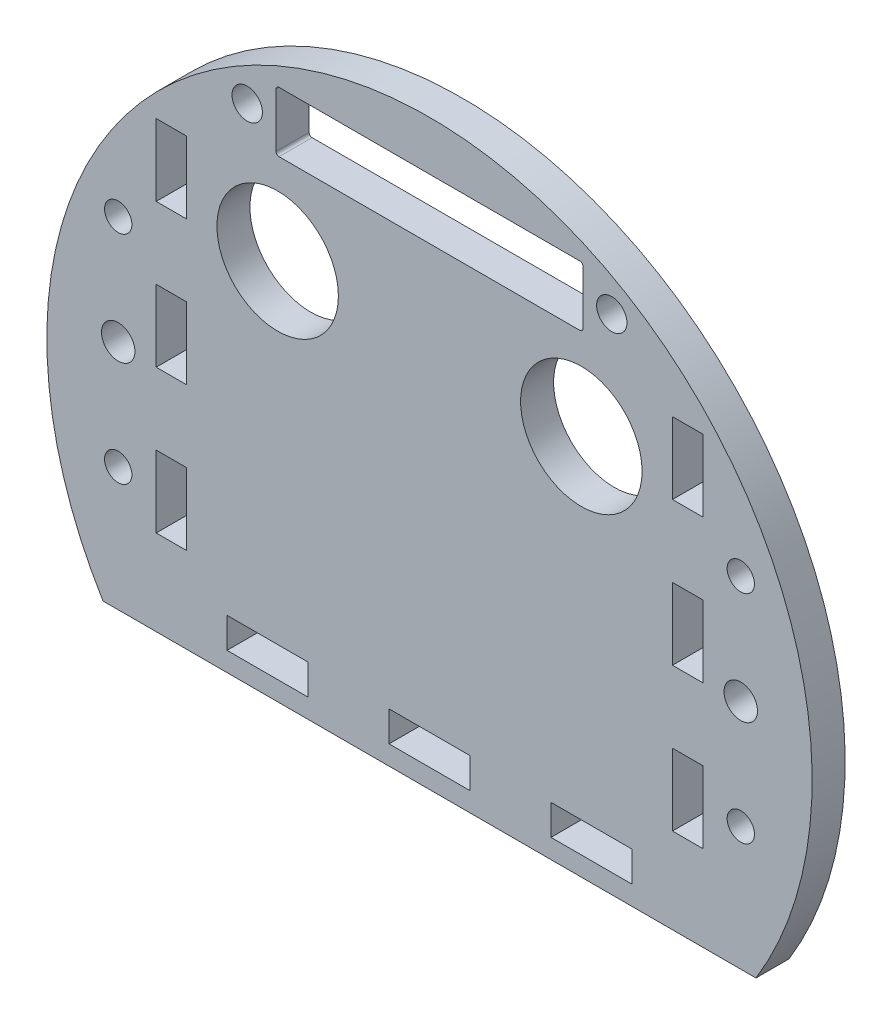
SolidWorks part; units mm, degrees
material "ABS"
ref_plane "Front Plane" through (0, 0, 0) normal (0, 0, 1) x (1, 0, 0)
ref_plane "Top Plane" through (0, 0, 0) normal (0, 1, 0) x (1, 0, 0)
ref_plane "Right Plane" through (0, 0, 0) normal (1, 0, 0) x (0, 0, -1)
sketch "Sketch1" plane through (0, 0, 0) normal (0, 0, 1) x (1, 0, 0)
  line L0 (0, 63) -> (0, -63) construction
  line L1 (-20, -29.6871) -> (-6.6667, -29.6871) construction
  line L2 (-40, -24.6913) -> (40, -24.6913) construction
  line L3 (-40, -24.6913) -> (-40, 40.3087) construction
  line L4 (-40, 40.3087) -> (40, 40.3087) construction
  line L5 (40, -24.6913) -> (40, 40.3087) construction
  line L6 (-40, -24.6913) -> (40, 40.3087) construction
  line L7 (-40, 40.3087) -> (40, -24.6913) construction
  line L8 (-24.765, 54.8734) -> (24.765, 54.8734)
  line L9 (-25.265, 54.3734) -> (-25.265, 45.4834)
  line L10 (-24.765, 44.9834) -> (24.765, 44.9834)
  line L11 (25.265, 54.3734) -> (25.265, 45.4834)
  line L12 (-25.265, 54.8734) -> (25.265, 44.9834) construction
  line L13 (-25.265, 44.9834) -> (25.265, 54.8734) construction
  line L14 (-37.5, -47.3621) -> (37.5, -47.3621) construction
  line L15 (-37.5, -47.3621) -> (-37.5, -32.8621) construction
  line L16 (-37.5, -32.8621) -> (37.5, -32.8621) construction
  line L17 (37.5, -47.3621) -> (37.5, -32.8621) construction
  line L18 (-37.5, -47.3621) -> (37.5, -32.8621) construction
  line L19 (-37.5, -32.8621) -> (37.5, -47.3621) construction
  line L32 (-33.3333, -24.6913) -> (-20, -24.6913)
  line L33 (-25.265, 54.8734) -> (-26.348, 57.2257) construction
  line L34 (-44.9958, 28.4905) -> (-44.9958, 16.6724) construction
  line L35 (-39.1075, -49.3923) -> (-37.5, -47.3621) construction
  line L36 (40, 40.3087) -> (44.9958, 40.3087)
  line L37 (40, 40.3087) -> (40, 28.4905)
  line L38 (40, 28.4905) -> (44.9958, 28.4905)
  line L39 (44.9958, 40.3087) -> (44.9958, 28.4905)
  line L40 (40, 16.6724) -> (44.9958, 16.6724)
  line L41 (40, 16.6724) -> (40, 4.8542)
  line L42 (40, 4.8542) -> (44.9958, 4.8542)
  line L43 (44.9958, 16.6724) -> (44.9958, 4.8542)
  line L44 (-40, 40.3087) -> (-44.9958, 40.3087)
  line L45 (-40, 40.3087) -> (-40, 28.4905)
  line L46 (-40, 28.4905) -> (-44.9958, 28.4905)
  line L47 (-44.9958, 40.3087) -> (-44.9958, 28.4905)
  line L48 (-40, 16.6724) -> (-44.9958, 16.6724)
  line L49 (-40, 16.6724) -> (-40, 4.8542)
  line L50 (-40, 4.8542) -> (-44.9958, 4.8542)
  line L51 (-44.9958, 16.6724) -> (-44.9958, 4.8542)
  line L52 (44.9958, 28.4905) -> (44.9958, 16.6724) construction
  line L53 (-44.9958, 4.8542) -> (-44.9958, -6.964) construction
  line L54 (-33.3333, -24.6913) -> (-33.3333, -29.6871)
  line L55 (44.9958, 4.8542) -> (44.9958, -6.964) construction
  line L56 (-44.9958, -6.964) -> (-40, -6.964)
  line L57 (-44.9958, 40.3087) -> (-46.9246, 42.0366) construction
  line L58 (-53.7502, -32.8621) -> (53.7502, -32.8621)
  line L59 (-30.0111, 49.9284) -> (30.0111, 49.9284) construction
  line L60 (-30.0111, 49.9284) -> (-32.4562, 53.9963) construction
  line L61 (-30.0111, 52.4284) -> (-25.265, 52.4284) construction
  line L62 (-44.9958, -6.964) -> (-44.9958, -18.7822)
  line L63 (-44.9958, -18.7822) -> (-40, -18.7822)
  line L64 (-40, -6.964) -> (-40, -18.7822)
  line L65 (44.9958, -6.964) -> (40, -6.964)
  line L66 (44.9958, -6.964) -> (44.9958, -18.7822)
  line L67 (44.9958, -18.7822) -> (40, -18.7822)
  line L68 (40, -6.964) -> (40, -18.7822)
  line L69 (-33.3333, -29.6871) -> (-20, -29.6871)
  line L70 (-20, -24.6913) -> (-20, -29.6871)
  line L71 (-6.6667, -24.6913) -> (6.6667, -24.6913)
  line L72 (-6.6667, -24.6913) -> (-6.6667, -29.6871)
  line L73 (-6.6667, -29.6871) -> (6.6667, -29.6871)
  line L74 (6.6667, -24.6913) -> (6.6667, -29.6871)
  line L75 (20, -24.6913) -> (33.3333, -24.6913)
  line L76 (20, -24.6913) -> (20, -29.6871)
  line L77 (20, -29.6871) -> (33.3333, -29.6871)
  line L78 (33.3333, -24.6913) -> (33.3333, -29.6871)
  line L79 (6.6667, -29.6871) -> (20, -29.6871) construction
  line L80 (6.6667, -27.1892) -> (13.3333, -27.1892) construction
  line L81 (13.3333, -27.1892) -> (20, -27.1892) construction
  line L82 (-33.3333, -29.6871) -> (-40, -29.6871) construction
  line L83 (-40, -29.6871) -> (-40, -24.6913) construction
  line L84 (33.3333, -29.6871) -> (40, -29.6871) construction
  line L85 (40, -29.6871) -> (40, -24.6913) construction
  line L86 (-44.9958, -18.7822) -> (-44.9958, -24.6913) construction
  line L87 (-44.9958, -24.6913) -> (-40, -24.6913) construction
  line L88 (44.9958, -18.7822) -> (44.9958, -24.6913) construction
  line L89 (44.9958, -24.6913) -> (40, -24.6913) construction
  line L90 (-42.4979, 4.8542) -> (-42.4979, -1.0549) construction
  line L91 (-42.4979, -1.0549) -> (-42.4979, -6.964) construction
  line L92 (-40, 40.3087) -> (-40, 44.9834) construction
  line L93 (-40, 44.9834) -> (-25.265, 44.9834) construction
  line L94 (25.265, 44.9834) -> (40, 44.9834) construction
  line L95 (40, 44.9834) -> (40, 40.3087) construction
  line L96 (-40, 44.9834) -> (-25, 29.9834) construction
  line L97 (-25, 29.9834) -> (25, 29.9834) construction
  line L98 (25, 29.9834) -> (40, 44.9834) construction
  arc A1 (53.7502, -32.8621) -> (-53.7502, -32.8621) centre (0, 0) ccw
  circle A2 centre (51.25, 23.184) radius 2.25 construction
  circle A3 centre (51.25, -12.4964) radius 2.25 construction
  circle A4 centre (-51.25, -12.4964) radius 2.25 construction
  circle A5 centre (-51.25, 23.184) radius 2.25 construction
  circle A6 centre (51.25, 23.184) radius 2.25
  circle A7 centre (51.25, -12.4964) radius 2.25
  circle A8 centre (-51.25, -12.4964) radius 2.25
  circle A9 centre (-51.25, 23.184) radius 2.25
  arc A10 (60.1885, -18.6102) -> (-6.6055, -62.6528) centre (0, 0) ccw construction
  circle A11 centre (-51.25, 5.3438) radius 2.75
  circle A12 centre (51.25, 5.3438) radius 2.75
  arc A15 (-53.7502, -32.8621) -> (-39.1075, -49.3923) centre (0, 0) ccw construction
  arc A16 (-39.1075, -49.3923) -> (0, -63) centre (0, 0) ccw construction
  arc A17 (0, -63) -> (53.7502, -32.8621) centre (0, 0) ccw construction
  circle A18 centre (-30.0111, 49.9284) radius 2.5
  circle A19 centre (30.0111, 49.9284) radius 2.5
  arc A20 (24.765, 44.9834) -> (25.265, 45.4834) centre (24.765, 45.4834) ccw
  arc A21 (24.765, 54.8734) -> (25.265, 54.3734) centre (24.765, 54.3734) cw
  arc A22 (-25.265, 54.3734) -> (-24.765, 54.8734) centre (-24.765, 54.3734) cw
  arc A23 (-25.265, 45.4834) -> (-24.765, 44.9834) centre (-24.765, 45.4834) ccw
  circle A24 centre (-25, 29.9834) radius 10
  circle A25 centre (25, 29.9834) radius 10
  circle A26 centre (-25, 29.9834) radius 15 construction
  point P26 (0, 7.8087)
  point P31 (0, 49.9284)
  point P36 (0, -40.1121)
  dimension "D1" = 5.5
  dimension "D2" = 50.53
  dimension "D10" = 5
  dimension "D11" = 0.5
  dimension "D12" = 20
  dimension "D13" = 5
  dimension "D3" = 9.89
  dimension "D4" = 65
  dimension "D5" = 80
  dimension "D6" = 75
  dimension "D7" = 14.5
  dimension "D8" = 4.9958
  dimension "D9" = 3.175
extrude "Boss-Extrude1" add sketch "Sketch1" along normal blind 5.4356
